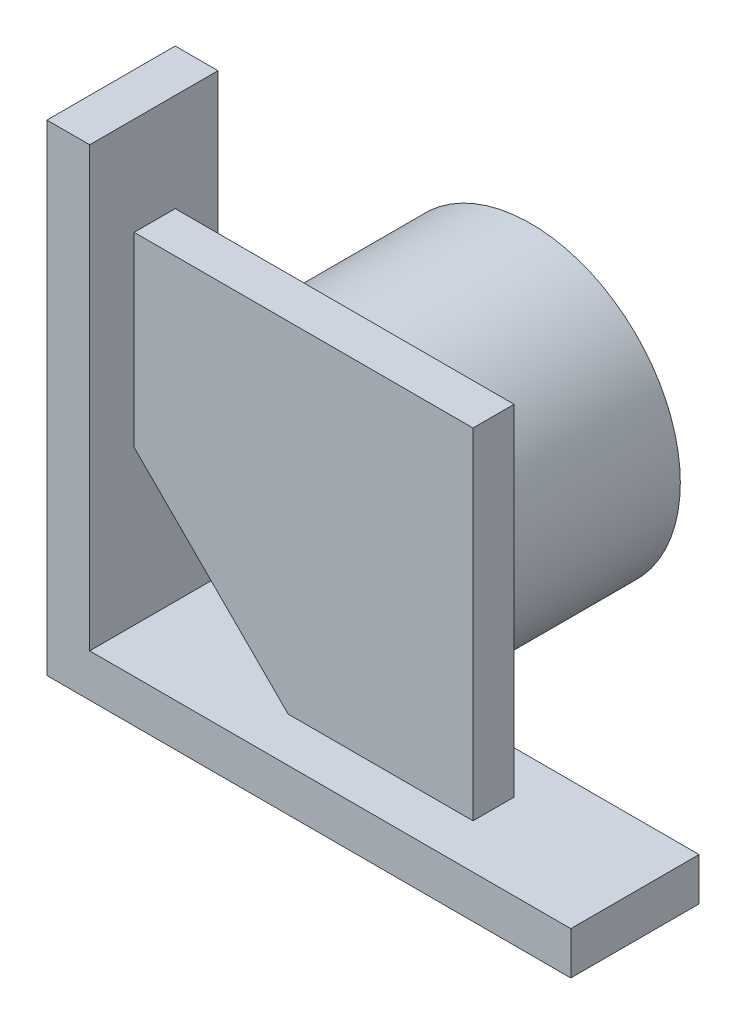
SolidWorks part; units mm, degrees
ref_plane "Front Plane" through (0, 0, 0) normal (0, 0, 1) x (1, 0, 0)
ref_plane "Top Plane" through (0, 0, 0) normal (0, 1, 0) x (1, 0, 0)
ref_plane "Right Plane" through (0, 0, 0) normal (1, 0, 0) x (0, 0, -1)
sketch "Sketch1" plane through (0, 0, 0) normal (-1, 0, 0) x (0, -1, 0)
  line L0 (0, -76.659) -> (0, 176.2699) construction
  line L1 (-45.4446, 0) -> (105.5783, 0) construction
  line L3 (0, 0) -> (-12.7, 0)
  line L4 (0, 0) -> (0, 38.1)
  line L5 (0, 38.1) -> (-12.7, 38.1)
  line L6 (-12.7, 0) -> (-12.7, 38.1)
  dimension "D1" = 38.1
  dimension "D2" = 12.7
extrude "Boss-Extrude1" add sketch "Sketch1" against normal blind 155.575
sketch "Sketch3" plane through (0, 12.7, 0) normal (0, 1, 0) x (1, 0, 0)
  line L0 (155.575, -38.1) -> (0, -38.1) construction
  line L1 (0, 0) -> (12.7, 0)
  line L2 (0, 0) -> (0, -38.1)
  line L3 (0, -38.1) -> (12.7, -38.1)
  line L4 (12.7, 0) -> (12.7, -38.1)
  dimension "D1" = 12.7
extrude "Boss-Extrude2" add sketch "Sketch3" along normal blind 130.175
sketch "Sketch4" plane through (0, 12.7, 0) normal (0, 1, 0) x (1, 0, 0)
  line L0 (12.7, -38.1) -> (12.7, 0) construction
  line L1 (12.7, -12.7) -> (113.3348, -12.7)
  line L2 (12.7, -12.7) -> (12.7, -24.892)
  line L3 (12.7, -24.892) -> (113.3348, -24.892)
  line L4 (113.3348, -12.7) -> (113.3348, -24.892)
  dimension "D1" = 100.6348
  dimension "D2" = 12.192
  dimension "D3" = 12.7
extrude "Boss-Extrude3" add sketch "Sketch4" along normal blind 101.0412
sketch "Sketch5" plane through (0, 0, 24.892) normal (0, 0, 1) x (1, 0, 0)
  line L0 (12.7, 58.42) -> (58.42, 12.7)
  line L1 (12.7, 113.7412) -> (12.7, 12.7) construction
  line L2 (155.575, 12.7) -> (12.7, 12.7) construction
  line L3 (58.42, 12.7) -> (12.7, 12.7)
  line L4 (12.7, 12.7) -> (12.7, 58.42)
  dimension "D1" = 45.72
  dimension "D2" = 45.72
sketch "Sketch7" plane through (0, 0, 0) normal (0, 1, 0) x (1, 0, 0)
  line L0 (0, 66.6649) -> (0, -63.5607) construction
  line L1 (-10.7252, 48.3616) -> (133.7438, 48.3616) construction
  line L2 (113.3348, -12.7) -> (12.7, -12.7) construction
  dimension "D1" = 61.0616
sketch "Sketch6" plane through (0, 0, 12.7) normal (0, 0, -1) x (-1, 0, 0)
  line L3 (-57.2008, 61.6364) -> (-57.2008, 4.9884) construction
  line L4 (-61.9953, 57.2008) -> (-4.3021, 57.2008) construction
  line L5 (-113.3348, 12.7) -> (-12.7, 12.7) construction
  line L6 (-12.7, 12.7) -> (-12.7, 58.42) construction
  circle A0 centre (-57.2008, 57.2008) radius 44.45
  circle A1 centre (-57.2008, 57.2008) radius 39.3192
  point P8 (-12.7508, 57.2008)
  point P9 (-57.2008, 12.7508)
  dimension "D1" = 88.9
  dimension "D3" = 0.0508
  dimension "D4" = 0.0508
  dimension "D2" = 5.1308
ref_plane "Plane1" through (0, 0, -48.3616) normal (0, 0, 1) x (1, 0, 0)
extrude "Cut-Extrude2" cut sketch "Sketch5" against normal up to surface (12.192 mm away) up to face at (63.0174, 63.2206, 12.7)
extrude "Boss-Extrude8" add sketch "Sketch6" against normal up to surface (61.0616 mm away) from surface at 61.0616 contours A0 A1 up to face at (62.0979, 62.2605, 12.7) starting at plane "Plane1"
